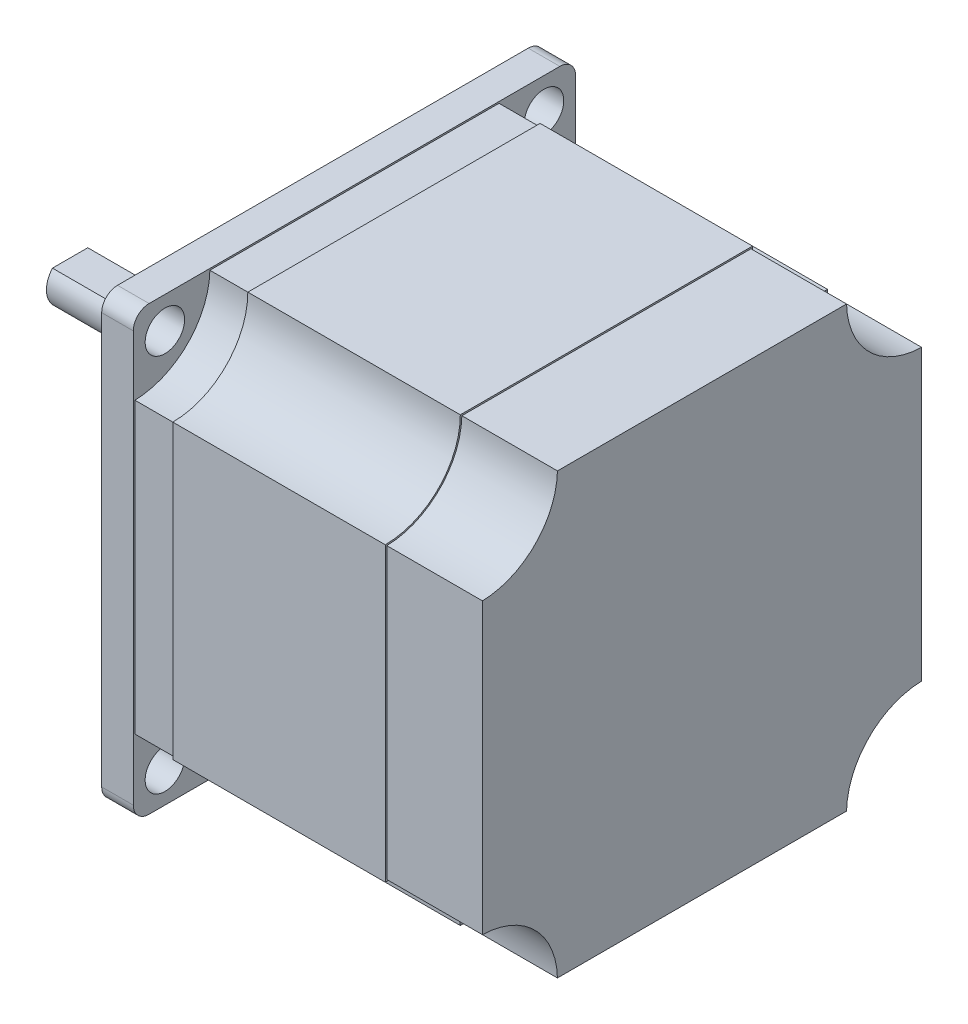
SolidWorks part; units mm, degrees
ref_plane "Front" through (0, 0, 0) normal (0, 0, 1) x (1, 0, 0)
ref_plane "Top" through (0, 0, 0) normal (0, 1, 0) x (1, 0, 0)
ref_plane "Right" through (0, 0, 0) normal (1, 0, 0) x (0, 0, -1)
sketch "Sketch1" plane through (0, 0, 0) normal (1, 0, 0) x (0, 0, -1)
  line L0 (-53.617, 0) -> (72.2837, 0) construction
  line L1 (-18.5, 28) -> (18.5, 28)
  line L2 (-28, 18.5) -> (-28, -18.5)
  line L3 (-18.5, -28) -> (18.5, -28)
  line L4 (28, 18.5) -> (28, -18.5)
  line L5 (-28, 28) -> (28, -28) construction
  line L6 (-28, -28) -> (28, 28) construction
  line L7 (0, 48.9504) -> (0, -61.2624) construction
  arc A0 (18.5, 28) -> (28, 18.5) centre (28, 28) ccw
  arc A1 (28, -18.5) -> (18.5, -28) centre (28, -28) ccw
  arc A2 (-18.5, -28) -> (-28, -18.5) centre (-28, -28) ccw
  arc A3 (-28, 18.5) -> (-18.5, 28) centre (-28, 28) ccw
  circle A4 centre (0, 0) radius 3
  point P0 (0, 0)
  point P19 (0, 0)
  dimension "D1" = 6
  dimension "D2" = 56
  dimension "D4" = 37
  dimension "D6" = 28
  dimension "D7" = 28
  dimension "D3" = 4
extrude "Boss-Extrude1" add sketch "Sketch1" along normal blind 27
sketch "Sketch6" plane through (27, 0, 0) normal (1, 0, 0) x (0, 0, -1)
  line L8 (18.3021, 27.8) -> (-18.3021, 27.8)
  line L9 (-27.8, 18.3021) -> (-27.8, -18.3021)
  line L10 (-18.3021, -27.8) -> (18.3021, -27.8)
  line L11 (27.8, -18.3021) -> (27.8, 18.3021)
  line L12 (18.3021, 27.8) -> (-18.3021, 27.8)
  line L13 (-27.8, 18.3021) -> (-27.8, -18.3021)
  line L14 (-18.3021, -27.8) -> (18.3021, -27.8)
  line L15 (27.8, -18.3021) -> (27.8, 18.3021)
  line L16 (28, -18.5) -> (28, 18.5)
  line L17 (-18.5, -28) -> (18.5, -28)
  line L18 (-28, 18.5) -> (-28, -18.5)
  line L19 (18.5, 28) -> (-18.5, 28)
  line L20 (28, -18.5) -> (28, 18.5)
  line L21 (-18.5, -28) -> (18.5, -28)
  line L22 (-28, 18.5) -> (-28, -18.5)
  line L23 (18.5, 28) -> (-18.5, 28)
  arc A8 (18.3021, 27.8) -> (27.8, 18.3021) centre (28, 28) ccw
  arc A9 (-27.8, 18.3021) -> (-18.3021, 27.8) centre (-28, 28) ccw
  arc A10 (-18.3021, -27.8) -> (-27.8, -18.3021) centre (-28, -28) ccw
  arc A11 (27.8, -18.3021) -> (18.3021, -27.8) centre (28, -28) ccw
  arc A12 (18.3021, 27.8) -> (27.8, 18.3021) centre (28, 28) ccw
  arc A13 (-27.8, 18.3021) -> (-18.3021, 27.8) centre (-28, 28) ccw
  arc A14 (-18.3021, -27.8) -> (-27.8, -18.3021) centre (-28, -28) ccw
  arc A15 (27.8, -18.3021) -> (18.3021, -27.8) centre (28, -28) ccw
  arc A16 (18.5, 28) -> (28, 18.5) centre (28, 28) ccw
  arc A17 (28, -18.5) -> (18.5, -28) centre (28, -28) ccw
  arc A18 (-18.5, -28) -> (-28, -18.5) centre (-28, -28) ccw
  arc A19 (-28, 18.5) -> (-18.5, 28) centre (-28, 28) ccw
  arc A20 (18.5, 28) -> (28, 18.5) centre (28, 28) ccw
  arc A21 (28, -18.5) -> (18.5, -28) centre (28, -28) ccw
  arc A22 (-18.5, -28) -> (-28, -18.5) centre (-28, -28) ccw
  arc A23 (-28, 18.5) -> (-18.5, 28) centre (-28, 28) ccw
  dimension "D1" = 0.2
  dimension "D2" = 0
extrude "Cut-Extrude4" cut sketch "Sketch6" against normal blind 0.1
sketch "Sketch10" plane through (27, 0, 0) normal (1, 0, 0) x (0, 0, -1)
  line L4 (27.8, -18.3021) -> (27.8, 18.3021)
  line L5 (27.8, -18.3021) -> (27.8, 18.3021)
  line L6 (18.3021, 27.8) -> (-18.3021, 27.8)
  line L7 (18.3021, 27.8) -> (-18.3021, 27.8)
  line L12 (-27.8, 18.3021) -> (-27.8, -18.3021)
  line L13 (-27.8, 18.3021) -> (-27.8, -18.3021)
  line L14 (-18.3021, -27.8) -> (18.3021, -27.8)
  line L15 (-18.3021, -27.8) -> (18.3021, -27.8)
  arc A4 (18.3021, 27.8) -> (27.8, 18.3021) centre (28, 28) ccw
  arc A5 (18.3021, 27.8) -> (27.8, 18.3021) centre (28, 28) ccw
  arc A6 (-27.8, 18.3021) -> (-18.3021, 27.8) centre (-28, 28) ccw
  arc A7 (-27.8, 18.3021) -> (-18.3021, 27.8) centre (-28, 28) ccw
  arc A12 (-18.3021, -27.8) -> (-27.8, -18.3021) centre (-28, -28) ccw
  arc A13 (-18.3021, -27.8) -> (-27.8, -18.3021) centre (-28, -28) ccw
  arc A14 (27.8, -18.3021) -> (18.3021, -27.8) centre (28, -28) ccw
  arc A15 (27.8, -18.3021) -> (18.3021, -27.8) centre (28, -28) ccw
  dimension "D1" = 0
extrude "Boss-Extrude4" add sketch "Sketch10" along normal blind 12
sketch "Sketch12" plane through (0, 0, 0) normal (-1, 0, 0) x (0, 0, 1)
  line L4 (-27.8, 18.3021) -> (-27.8, -18.3021)
  line L5 (18.3021, 27.8) -> (-18.3021, 27.8)
  line L6 (27.8, -18.3021) -> (27.8, 18.3021)
  line L7 (-18.3021, -27.8) -> (18.3021, -27.8)
  line L8 (-27.8, 18.3021) -> (-27.8, -18.3021)
  line L9 (18.3021, 27.8) -> (-18.3021, 27.8)
  line L10 (27.8, -18.3021) -> (27.8, 18.3021)
  line L11 (-18.3021, -27.8) -> (18.3021, -27.8)
  arc A4 (-18.3021, -27.8) -> (-27.8, -18.3021) centre (-28, -28) ccw
  arc A5 (-27.8, 18.3021) -> (-18.3021, 27.8) centre (-28, 28) ccw
  arc A6 (18.3021, 27.8) -> (27.8, 18.3021) centre (28, 28) ccw
  arc A7 (27.8, -18.3021) -> (18.3021, -27.8) centre (28, -28) ccw
  arc A8 (-18.3021, -27.8) -> (-27.8, -18.3021) centre (-28, -28) ccw
  arc A9 (-27.8, 18.3021) -> (-18.3021, 27.8) centre (-28, 28) ccw
  arc A10 (18.3021, 27.8) -> (27.8, 18.3021) centre (28, 28) ccw
  arc A11 (27.8, -18.3021) -> (18.3021, -27.8) centre (28, -28) ccw
  dimension "D1" = 0
extrude "Boss-Extrude5" add sketch "Sketch12" along normal blind 5
sketch "Sketch14" plane through (-5, 0, 0) normal (-1, 0, 0) x (0, 0, 1)
  line L1 (-26, 28) -> (26, 28)
  line L2 (-28, 26) -> (-28, -26)
  line L3 (-26, -28) -> (26, -28)
  line L4 (28, 26) -> (28, -26)
  line L5 (-28, 28) -> (28, -28) construction
  line L6 (-28, -28) -> (28, 28) construction
  arc A0 (-28, -26) -> (-26, -28) centre (-26, -26) ccw
  arc A1 (26, -28) -> (28, -26) centre (26, -26) ccw
  arc A2 (28, 26) -> (26, 28) centre (26, 26) ccw
  arc A3 (-28, 26) -> (-26, 28) centre (-26, 26) cw
  circle A5 centre (-24, 24) radius 2.5
  circle A6 centre (24, 24) radius 2.5
  circle A7 centre (24, -24) radius 2.5
  circle A8 centre (-24, -24) radius 2.5
  point P0 (0, 0)
  point P30 (0, 0)
  dimension "D1" = 2
  dimension "D4" = 24
  dimension "D5" = 5
  dimension "D6" = 4
  dimension "D2" = 56
  dimension "D3" = 56
extrude "Boss-Extrude7" add sketch "Sketch14" along normal blind 4
sketch "Sketch15" plane through (-9, 0, 0) normal (-1, 0, 0) x (0, 0, 1)
  circle A0 centre (0, 0) radius 19
  dimension "D1" = 38
extrude "Boss-Extrude8" add sketch "Sketch15" along normal blind 2
sketch "Sketch16" plane through (-11, 0, 0) normal (-1, 0, 0) x (0, 0, 1)
  circle A0 centre (0, 0) radius 3
  dimension "D1" = 6
extrude "Boss-Extrude9" add sketch "Sketch16" along normal blind 30
sketch "Sketch17" plane through (-41, 0, 0) normal (-1, 0, 0) x (0, 0, 1)
  line L0 (0, 0) -> (0, 11.872) construction
  line L1 (3, 2) -> (-3, 2)
  line L2 (-3, 2) -> (-3, 8)
  line L3 (-3, 8) -> (3, 8)
  line L4 (3, 2) -> (3, 8)
  circle A0 centre (0, 0) radius 3 construction
  point P8 (0, 8)
  point P9 (0, 2)
  dimension "D1" = 2
  dimension "D2" = 6
  dimension "D3" = 6
extrude "Cut-Extrude5" cut sketch "Sketch17" against normal blind 20
